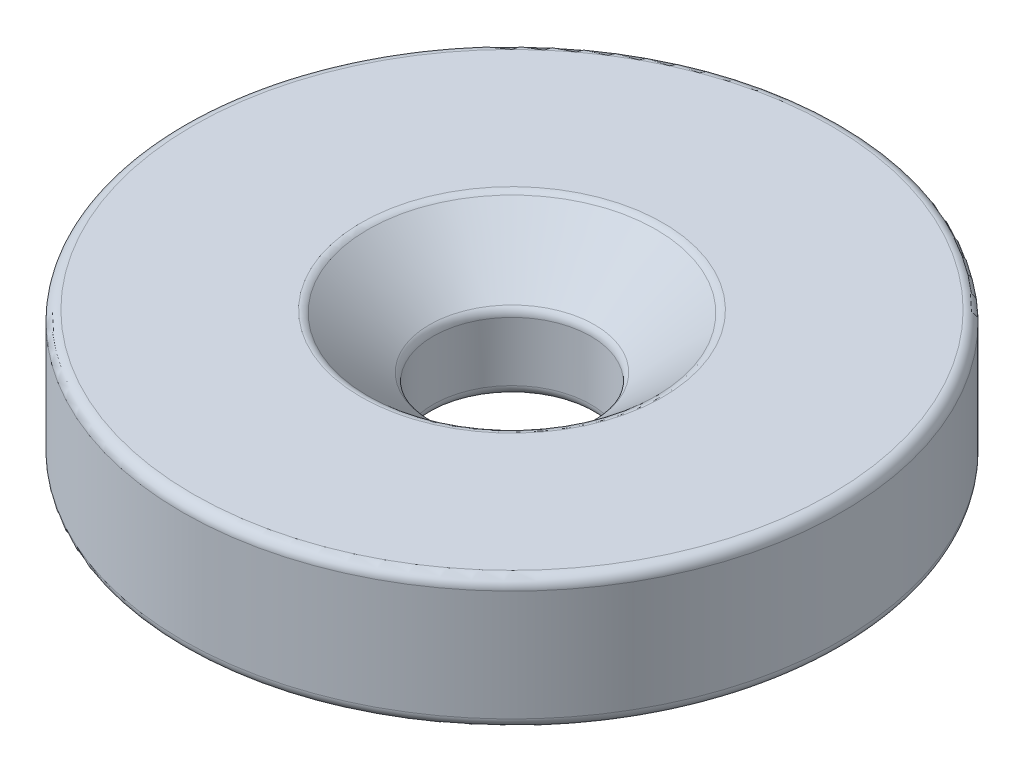
SolidWorks part; units mm, degrees
material "Alloy Steel"
ref_plane "Front Plane" through (0, 0, 0) normal (0, 0, 1) x (1, 0, 0)
ref_plane "Top Plane" through (0, 0, 0) normal (0, 1, 0) x (1, 0, 0)
ref_plane "Right Plane" through (0, 0, 0) normal (1, 0, 0) x (0, 0, -1)
sketch "Sketch1" plane through (0, 0, 0) normal (0, 1, 0) x (1, 0, 0)
  circle A1 centre (0, 0) radius 7.9375
  dimension "D1" = 15.875
extrude "Boss-Extrude1" add sketch "Sketch1" along normal mid plane 3.175
hole_wizard "CSK for #6 Flat Head Machine Screw (100)1" positions "Sketch2" profile "Sketch3" countersink size "#6" standard "ANSI Inch" end condition through all
sketch "Sketch2" plane through (0, 1.5875, 0) normal (0, 1, 0) x (1, 0, 0)
  point P0 (0, 0)
sketch "Sketch3" plane through (0, 1.5875, 0) normal (1, 0, 0) x (0, 0, 1)
  line L0 (0, 0) -> (0, 3.175)
  line L1 (0, 3.175) -> (1.8986, 3.175)
  line L2 (1.8986, 3.175) -> (1.8986, 1.38)
  line L3 (1.8986, 1.38) -> (3.5433, 0)
  line L5 (3.5433, 0) -> (0, 0)
  line L6 (-1.8986, 1.38) -> (-3.5433, 0) construction
  line L11 (0, -6.35) -> (0, 107.95) construction
  dimension "Thru Hole Dia." = 3.7973
  dimension "Thru Hole Depth" = 3.175
  dimension "Near C'Sink Dia." = 7.0866
  dimension "Near C'Sink Angle" = 100
fillet "Fillet1" radius 0.254 5 edges at (0, 1.5875, 3.5433) (0, 0.2075, 1.8986) (0, -1.5875, 1.8986) (0, -1.5875, 7.9375) (0, 1.5875, 7.9375)
